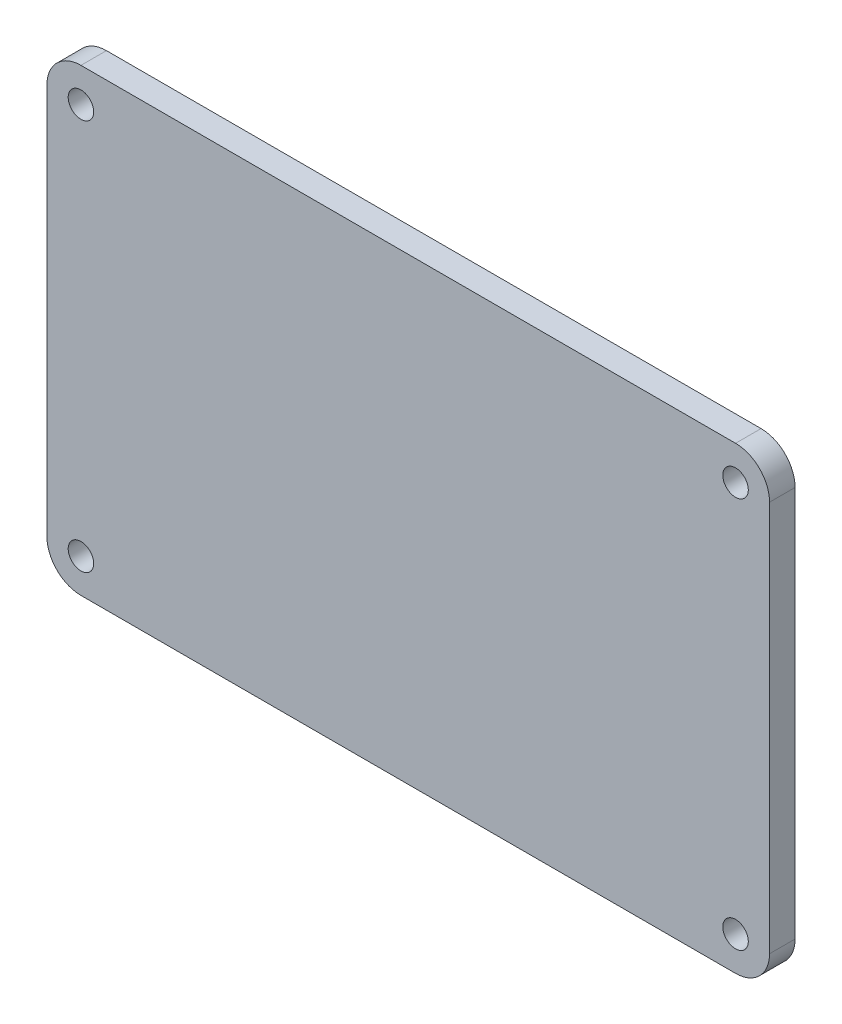
SolidWorks part; units mm, degrees
material "Acrylique (impact moyen-haut)"
ref_plane "Plan de face" through (0, 0, 0) normal (0, 0, 1) x (1, 0, 0)
ref_plane "Plan de dessus" through (0, 0, 0) normal (0, 1, 0) x (1, 0, 0)
ref_plane "Plan de droite" through (0, 0, 0) normal (1, 0, 0) x (0, 0, -1)
sketch "Esquisse1" plane through (141.9201, 723.1226, -1989.5789) normal (0, 0, 1) x (1, 0, 0)
  line L0 (-35.1306, 25.1234) -> (41.8694, 25.1234)
  line L1 (45.8694, 21.1234) -> (45.8694, -24.8766)
  line L2 (41.8694, -28.8766) -> (-35.1306, -28.8766)
  line L3 (-39.1306, 21.1234) -> (-39.1306, -24.8766)
  arc A0 (-35.1306, 25.1234) -> (-39.1306, 21.1234) centre (-35.1306, 21.1234) ccw
  arc A1 (41.8694, 25.1234) -> (45.8694, 21.1234) centre (41.8694, 21.1234) cw
  arc A2 (41.8694, -28.8766) -> (45.8694, -24.8766) centre (41.8694, -24.8766) ccw
  arc A3 (-39.1306, -24.8766) -> (-35.1306, -28.8766) centre (-35.1306, -24.8766) ccw
  circle A4 centre (-35.1306, -24.8766) radius 1.5
  circle A5 centre (-35.1306, 21.1234) radius 1.5
  circle A6 centre (41.8694, 21.1234) radius 1.5
  circle A7 centre (41.8694, -24.8766) radius 1.5
extrude "Boss.-Extru.1" add sketch "Esquisse1" along normal blind 3
